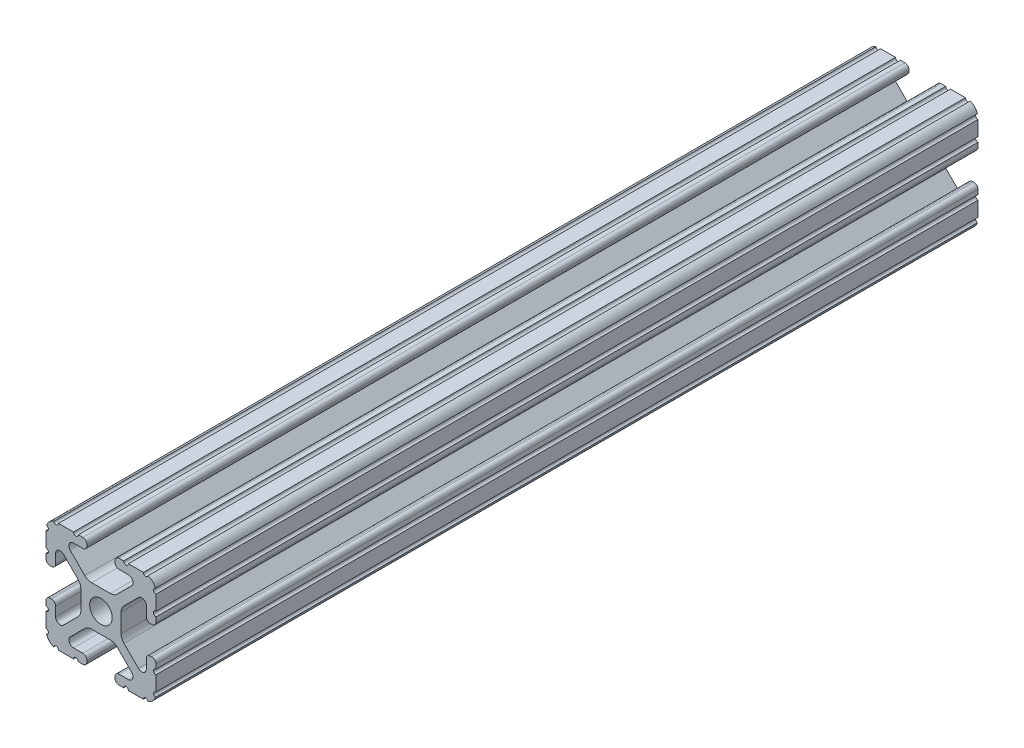
SolidWorks part; units mm, degrees
ref_plane "Front Plane" through (0, 0, 0) normal (0, 0, 1) x (1, 0, 0)
ref_plane "Top Plane" through (0, 0, 0) normal (0, 1, 0) x (1, 0, 0)
ref_plane "Right Plane" through (0, 0, 0) normal (1, 0, 0) x (0, 0, -1)
sketch "Sketch2" plane through (0, 0, 0) normal (0, 0, 1) x (1, 0, 0)
  line L0 (0, 12.7) -> (0, -12.7) construction
  line L1 (-12.7, 0) -> (12.7, 0) construction
  line L2 (3.2512, -12.7) -> (12.7, -12.7)
  line L3 (12.7, -12.7) -> (12.7, -3.2512)
  line L4 (3.2512, -12.7) -> (3.2512, -10.4902)
  line L5 (3.2512, -10.4902) -> (8.9276, -10.4902)
  line L6 (8.9276, -10.4902) -> (3.0856, -4.6482)
  line L7 (0, 0) -> (12.7, -12.7) construction
  line L8 (12.7, -3.2512) -> (10.4902, -3.2512)
  line L9 (10.4902, -3.2512) -> (10.4902, -8.9276)
  line L10 (10.4902, -8.9276) -> (4.6482, -3.0856)
  circle A0 centre (0, 0) radius 2.6035
  arc A1 (6.3485, -10.4902) -> (7.1039, -8.6665) centre (6.3485, -9.4219) ccw construction
  point P8 (0, -4.6482)
  dimension "Center Hole Diameter" = 5.207
  dimension "Rail Height" = 25.4
  dimension "Rail Width" = 25.4
  dimension "T-Slot Width" = 6.5024
  dimension "Slot Inner Width" = 14.8336
  dimension "Thickness" = 2.2098
  dimension "Slot Depth" = 5.842
  dimension "D1" = 2.2098
sketch "Sketch3" plane through (0, 0, 0) normal (1, 0, 0) x (0, 0, -1)
  line L0 (-94.9961, -12.7) -> (94.9961, -12.7) construction
  line L1 (-69.5961, 0) -> (69.5961, 0) construction
  line L3 (94.9961, 0) -> (-94.9961, 0) construction
sketch "Sketch4" plane through (0, 0, 0) normal (0, 0, 1) x (1, 0, 0)
  line L0 (4.1904, -12.7) -> (10.1173, -12.7)
  line L1 (3.2512, -12.7) -> (12.7, -12.7) construction
  line L2 (3.2512, -12.7) -> (3.2512, -10.4902) construction
  line L3 (3.2512, -10.4902) -> (8.9276, -10.4902) construction
  line L4 (3.2512, -11.4294) -> (3.2512, -11.7608)
  line L5 (4.1904, -10.4902) -> (6.3485, -10.4902)
  line L6 (0, -4.6482) -> (2.164, -4.6482)
  line L7 (8.9276, -10.4902) -> (3.0856, -4.6482) construction
  line L8 (3.7373, -5.2999) -> (7.1039, -8.6665)
  line L9 (12.7, -12.7) -> (12.7, -3.2512) construction
  line L10 (10.4902, -8.9276) -> (4.6482, -3.0856) construction
  line L11 (10.4902, -3.2512) -> (10.4902, -8.9276) construction
  line L12 (10.4902, -6.3485) -> (10.4902, -4.1904)
  line L13 (12.7, -3.2512) -> (10.4902, -3.2512) construction
  line L14 (11.4294, -3.2512) -> (11.7608, -3.2512)
  line L15 (12.7, -4.1904) -> (12.7, -10.1173)
  line L16 (8.6665, -7.1039) -> (5.2999, -3.7373)
  line L17 (4.6482, 0) -> (4.6482, -2.164)
  line L18 (-12.7, 0) -> (12.7, 0) construction
  line L19 (0, -4.6482) -> (0, -2.6035)
  line L20 (0, 12.7) -> (0, -12.7) construction
  line L21 (4.6482, 0) -> (2.6035, 0)
  arc A0 (3.2512, -11.7608) -> (4.1904, -12.7) centre (4.1904, -11.7608) ccw
  arc A2 (3.2512, -11.4294) -> (4.1904, -10.4902) centre (4.1904, -11.4294) cw
  arc A3 (6.3485, -10.4902) -> (7.1039, -8.6665) centre (6.3485, -9.4219) ccw
  arc A4 (2.164, -4.6482) -> (3.7373, -5.2999) centre (2.164, -6.8732) cw
  arc A5 (10.1173, -12.7) -> (12.7, -10.1173) centre (10.1173, -10.1173) ccw
  arc A6 (8.6665, -7.1039) -> (10.4902, -6.3485) centre (9.4219, -6.3485) ccw
  arc A7 (10.4902, -4.1904) -> (11.4294, -3.2512) centre (11.4294, -4.1904) cw
  arc A8 (11.7608, -3.2512) -> (12.7, -4.1904) centre (11.7608, -4.1904) cw
  arc A9 (5.2999, -3.7373) -> (4.6482, -2.164) centre (6.8732, -2.164) cw
  circle A10 centre (0, 0) radius 2.6035 construction
  arc A11 (0, -2.6035) -> (2.6035, 0) centre (0, 0) ccw
  dimension "D1" = 2.5827
  dimension "D2" = 2.225
  dimension "D3" = 0.9392
extrude "Boss-Extrude1" add sketch "Sketch4" along normal up to vertex (94.9961 mm away) from vertex at -94.9961 starting at point (0, -12.7, -94.9961)
sketch "Sketch5" plane through (0, 0, 0) normal (0, 0, 1) x (1, 0, 0)
  line L0 (3.2512, -12.7) -> (12.7, -12.7) construction
  line L1 (4.1904, -10.4902) -> (6.3485, -10.4902) construction
  line L3 (0, 0) -> (12.7, -12.7) construction
  line L4 (6.3485, -10.4902) -> (6.3485, -12.7) construction
  line L5 (8.9276, -10.4902) -> (3.0856, -4.6482) construction
  circle A0 centre (10.3562, -12.7) radius 0.5524
  circle A1 centre (5.796, -12.7) radius 0.5524
  circle A2 centre (12.7, -10.3562) radius 0.5524
  circle A3 centre (12.7, -5.796) radius 0.5524
  point P10 (5.2694, -10.4902)
  point P12 (9.4219, -6.3485)
  dimension "D1" = 1.1049
extrude "Cut-Extrude1" cut sketch "Sketch5" against normal through all both and the other way through all
mirror "Mirror1" about plane through (0, 0, 0) normal (1, 0, 0) of bodies 137 134
mirror "Mirror2" about plane through (0, 0, 0) normal (0, 1, 0) of bodies 135
equation "\"D1@Sketch2\"=\"Thickness@Sketch2\""
equation "\"D2@Sketch4\"=\"Slot Inner Width@Sketch2\"*0.15"
equation "\"D1@Sketch4\"=\"D3@Sketch4\"*2.75"
equation "\"D3@Sketch4\"=\"Thickness@Sketch2\"*0.425"
equation "\"D1@Sketch5\"=\"Thickness@Sketch2\"*0.5"
equation "\"D1@Boss-Extrude1\"=\"Length@Sketch3\""
